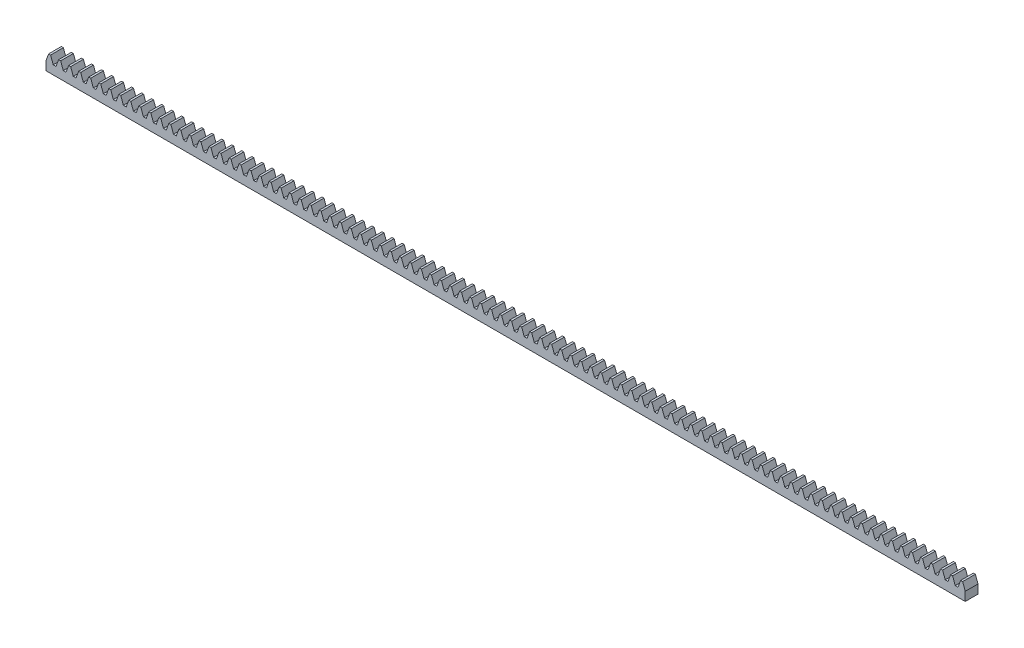
SolidWorks part; units mm, degrees
ref_plane "Front Plane" through (0, 0, 0) normal (0, 0, 1) x (1, 0, 0)
ref_plane "Top Plane" through (0, 0, 0) normal (0, 1, 0) x (1, 0, 0)
ref_plane "Right Plane" through (0, 0, 0) normal (1, 0, 0) x (0, 0, -1)
ref_plane "Plane1" through (0, 0, 46.6167) normal (0, 0, -1) x (-1, 0, 0)
sketch "Sketch1" plane through (0, 0, 46.6167) normal (0, 0, -1) x (-1, 0, 0)
  line L0 (-180.7837, -31.4854) -> (-182.0774, -35.0398)
  line L1 (-182.0774, -35.0398) -> (-182.0774, -39.4229)
  line L2 (-182.0774, -39.4229) -> (325.9226, -39.4229)
  line L3 (325.9226, -39.4229) -> (325.9226, -35.0573)
  line L4 (325.9226, -35.0573) -> (325.2266, -35.0573)
  line L5 (325.2266, -35.0573) -> (323.9265, -31.4854)
  line L6 (323.9265, -31.4854) -> (322.9314, -31.4854)
  line L7 (322.9314, -31.4854) -> (321.6313, -35.0573)
  line L8 (321.6313, -35.0573) -> (320.2393, -35.0573)
  line L9 (320.2393, -35.0573) -> (318.9392, -31.4854)
  line L10 (318.9392, -31.4854) -> (317.9441, -31.4854)
  line L11 (317.9441, -31.4854) -> (316.644, -35.0573)
  line L12 (316.644, -35.0573) -> (315.252, -35.0573)
  line L13 (315.252, -35.0573) -> (313.952, -31.4854)
  line L14 (313.952, -31.4854) -> (312.9568, -31.4854)
  line L15 (312.9568, -31.4854) -> (311.6568, -35.0573)
  line L16 (311.6568, -35.0573) -> (310.2647, -35.0573)
  line L17 (310.2647, -35.0573) -> (308.9647, -31.4854)
  line L18 (308.9647, -31.4854) -> (307.9695, -31.4854)
  line L19 (307.9695, -31.4854) -> (306.6695, -35.0573)
  line L20 (306.6695, -35.0573) -> (305.2775, -35.0573)
  line L21 (305.2775, -35.0573) -> (303.9774, -31.4854)
  line L22 (303.9774, -31.4854) -> (302.9823, -31.4854)
  line L23 (302.9823, -31.4854) -> (301.6822, -35.0573)
  line L24 (301.6822, -35.0573) -> (300.2902, -35.0573)
  line L25 (300.2902, -35.0573) -> (298.9901, -31.4854)
  line L26 (298.9901, -31.4854) -> (297.995, -31.4854)
  line L27 (297.995, -31.4854) -> (296.6949, -35.0573)
  line L28 (296.6949, -35.0573) -> (295.3029, -35.0573)
  line L29 (295.3029, -35.0573) -> (294.0028, -31.4854)
  line L30 (294.0028, -31.4854) -> (293.0077, -31.4854)
  line L31 (293.0077, -31.4854) -> (291.7076, -35.0573)
  line L32 (291.7076, -35.0573) -> (290.3156, -35.0573)
  line L33 (290.3156, -35.0573) -> (289.0156, -31.4854)
  line L34 (289.0156, -31.4854) -> (288.0204, -31.4854)
  line L35 (288.0204, -31.4854) -> (286.7204, -35.0573)
  line L36 (286.7204, -35.0573) -> (285.3283, -35.0573)
  line L37 (285.3283, -35.0573) -> (284.0283, -31.4854)
  line L38 (284.0283, -31.4854) -> (283.0331, -31.4854)
  line L39 (283.0331, -31.4854) -> (281.7331, -35.0573)
  line L40 (281.7331, -35.0573) -> (280.3411, -35.0573)
  line L41 (280.3411, -35.0573) -> (279.041, -31.4854)
  line L42 (279.041, -31.4854) -> (278.0459, -31.4854)
  line L43 (278.0459, -31.4854) -> (276.7458, -35.0573)
  line L44 (276.7458, -35.0573) -> (275.3538, -35.0573)
  line L45 (275.3538, -35.0573) -> (274.0537, -31.4854)
  line L46 (274.0537, -31.4854) -> (273.0586, -31.4854)
  line L47 (273.0586, -31.4854) -> (271.7585, -35.0573)
  line L48 (271.7585, -35.0573) -> (270.3665, -35.0573)
  line L49 (270.3665, -35.0573) -> (269.0664, -31.4854)
  line L50 (269.0664, -31.4854) -> (268.0713, -31.4854)
  line L51 (268.0713, -31.4854) -> (266.7713, -35.0573)
  line L52 (266.7713, -35.0573) -> (265.3792, -35.0573)
  line L53 (265.3792, -35.0573) -> (264.0792, -31.4854)
  line L54 (264.0792, -31.4854) -> (263.084, -31.4854)
  line L55 (263.084, -31.4854) -> (261.784, -35.0573)
  line L56 (261.784, -35.0573) -> (260.3919, -35.0573)
  line L57 (260.3919, -35.0573) -> (259.0919, -31.4854)
  line L58 (259.0919, -31.4854) -> (258.0968, -31.4854)
  line L59 (258.0968, -31.4854) -> (256.7967, -35.0573)
  line L60 (256.7967, -35.0573) -> (255.4047, -35.0573)
  line L61 (255.4047, -35.0573) -> (254.1046, -31.4854)
  line L62 (254.1046, -31.4854) -> (253.1095, -31.4854)
  line L63 (253.1095, -31.4854) -> (251.8094, -35.0573)
  line L64 (251.8094, -35.0573) -> (250.4174, -35.0573)
  line L65 (250.4174, -35.0573) -> (249.1173, -31.4854)
  line L66 (249.1173, -31.4854) -> (248.1222, -31.4854)
  line L67 (248.1222, -31.4854) -> (246.8221, -35.0573)
  line L68 (246.8221, -35.0573) -> (245.4301, -35.0573)
  line L69 (245.4301, -35.0573) -> (244.1301, -31.4854)
  line L70 (244.1301, -31.4854) -> (243.1349, -31.4854)
  line L71 (243.1349, -31.4854) -> (241.8349, -35.0573)
  line L72 (241.8349, -35.0573) -> (240.4428, -35.0573)
  line L73 (240.4428, -35.0573) -> (239.1428, -31.4854)
  line L74 (239.1428, -31.4854) -> (238.1476, -31.4854)
  line L75 (238.1476, -31.4854) -> (236.8476, -35.0573)
  line L76 (236.8476, -35.0573) -> (235.4556, -35.0573)
  line L77 (235.4556, -35.0573) -> (234.1555, -31.4854)
  line L78 (234.1555, -31.4854) -> (233.1604, -31.4854)
  line L79 (233.1604, -31.4854) -> (231.8603, -35.0573)
  line L80 (231.8603, -35.0573) -> (230.4683, -35.0573)
  line L81 (230.4683, -35.0573) -> (229.1682, -31.4854)
  line L82 (229.1682, -31.4854) -> (228.1731, -31.4854)
  line L83 (228.1731, -31.4854) -> (226.873, -35.0573)
  line L84 (226.873, -35.0573) -> (225.481, -35.0573)
  line L85 (225.481, -35.0573) -> (224.1809, -31.4854)
  line L86 (224.1809, -31.4854) -> (223.1858, -31.4854)
  line L87 (223.1858, -31.4854) -> (221.8858, -35.0573)
  line L88 (221.8858, -35.0573) -> (220.4937, -35.0573)
  line L89 (220.4937, -35.0573) -> (219.1937, -31.4854)
  line L90 (219.1937, -31.4854) -> (218.1985, -31.4854)
  line L91 (218.1985, -31.4854) -> (216.8985, -35.0573)
  line L92 (216.8985, -35.0573) -> (215.5064, -35.0573)
  line L93 (215.5064, -35.0573) -> (214.2064, -31.4854)
  line L94 (214.2064, -31.4854) -> (213.2113, -31.4854)
  line L95 (213.2113, -31.4854) -> (211.9112, -35.0573)
  line L96 (211.9112, -35.0573) -> (210.5192, -35.0573)
  line L97 (210.5192, -35.0573) -> (209.2191, -31.4854)
  line L98 (209.2191, -31.4854) -> (208.224, -31.4854)
  line L99 (208.224, -31.4854) -> (206.9239, -35.0573)
  line L100 (206.9239, -35.0573) -> (205.5319, -35.0573)
  line L101 (205.5319, -35.0573) -> (204.2318, -31.4854)
  line L102 (204.2318, -31.4854) -> (203.2367, -31.4854)
  line L103 (203.2367, -31.4854) -> (201.9366, -35.0573)
  line L104 (201.9366, -35.0573) -> (200.5446, -35.0573)
  line L105 (200.5446, -35.0573) -> (199.2446, -31.4854)
  line L106 (199.2446, -31.4854) -> (198.2494, -31.4854)
  line L107 (198.2494, -31.4854) -> (196.9494, -35.0573)
  line L108 (196.9494, -35.0573) -> (195.5573, -35.0573)
  line L109 (195.5573, -35.0573) -> (194.2573, -31.4854)
  line L110 (194.2573, -31.4854) -> (193.2621, -31.4854)
  line L111 (193.2621, -31.4854) -> (191.9621, -35.0573)
  line L112 (191.9621, -35.0573) -> (190.5701, -35.0573)
  line L113 (190.5701, -35.0573) -> (189.27, -31.4854)
  line L114 (189.27, -31.4854) -> (188.2749, -31.4854)
  line L115 (188.2749, -31.4854) -> (186.9748, -35.0573)
  line L116 (186.9748, -35.0573) -> (185.5828, -35.0573)
  line L117 (185.5828, -35.0573) -> (184.2827, -31.4854)
  line L118 (184.2827, -31.4854) -> (183.2876, -31.4854)
  line L119 (183.2876, -31.4854) -> (181.9875, -35.0573)
  line L120 (181.9875, -35.0573) -> (180.5955, -35.0573)
  line L121 (180.5955, -35.0573) -> (179.2954, -31.4854)
  line L122 (179.2954, -31.4854) -> (178.3003, -31.4854)
  line L123 (178.3003, -31.4854) -> (177.0002, -35.0573)
  line L124 (177.0002, -35.0573) -> (175.6082, -35.0573)
  line L125 (175.6082, -35.0573) -> (174.3082, -31.4854)
  line L126 (174.3082, -31.4854) -> (173.313, -31.4854)
  line L127 (173.313, -31.4854) -> (172.013, -35.0573)
  line L128 (172.013, -35.0573) -> (170.6209, -35.0573)
  line L129 (170.6209, -35.0573) -> (169.3209, -31.4854)
  line L130 (169.3209, -31.4854) -> (168.3257, -31.4854)
  line L131 (168.3257, -31.4854) -> (167.0257, -35.0573)
  line L132 (167.0257, -35.0573) -> (165.6337, -35.0573)
  line L133 (165.6337, -35.0573) -> (164.3336, -31.4854)
  line L134 (164.3336, -31.4854) -> (163.3385, -31.4854)
  line L135 (163.3385, -31.4854) -> (162.0384, -35.0573)
  line L136 (162.0384, -35.0573) -> (160.6464, -35.0573)
  line L137 (160.6464, -35.0573) -> (159.3463, -31.4854)
  line L138 (159.3463, -31.4854) -> (158.3512, -31.4854)
  line L139 (158.3512, -31.4854) -> (157.0511, -35.0573)
  line L140 (157.0511, -35.0573) -> (155.6591, -35.0573)
  line L141 (155.6591, -35.0573) -> (154.359, -31.4854)
  line L142 (154.359, -31.4854) -> (153.3639, -31.4854)
  line L143 (153.3639, -31.4854) -> (152.0639, -35.0573)
  line L144 (152.0639, -35.0573) -> (150.6718, -35.0573)
  line L145 (150.6718, -35.0573) -> (149.3718, -31.4854)
  line L146 (149.3718, -31.4854) -> (148.3766, -31.4854)
  line L147 (148.3766, -31.4854) -> (147.0766, -35.0573)
  line L148 (147.0766, -35.0573) -> (145.6845, -35.0573)
  line L149 (145.6845, -35.0573) -> (144.3845, -31.4854)
  line L150 (144.3845, -31.4854) -> (143.3894, -31.4854)
  line L151 (143.3894, -31.4854) -> (142.0893, -35.0573)
  line L152 (142.0893, -35.0573) -> (140.6973, -35.0573)
  line L153 (140.6973, -35.0573) -> (139.3972, -31.4854)
  line L154 (139.3972, -31.4854) -> (138.4021, -31.4854)
  line L155 (138.4021, -31.4854) -> (137.102, -35.0573)
  line L156 (137.102, -35.0573) -> (135.71, -35.0573)
  line L157 (135.71, -35.0573) -> (134.4099, -31.4854)
  line L158 (134.4099, -31.4854) -> (133.4148, -31.4854)
  line L159 (133.4148, -31.4854) -> (132.1147, -35.0573)
  line L160 (132.1147, -35.0573) -> (130.7227, -35.0573)
  line L161 (130.7227, -35.0573) -> (129.4227, -31.4854)
  line L162 (129.4227, -31.4854) -> (128.4275, -31.4854)
  line L163 (128.4275, -31.4854) -> (127.1275, -35.0573)
  line L164 (127.1275, -35.0573) -> (125.7354, -35.0573)
  line L165 (125.7354, -35.0573) -> (124.4354, -31.4854)
  line L166 (124.4354, -31.4854) -> (123.4402, -31.4854)
  line L167 (123.4402, -31.4854) -> (122.1402, -35.0573)
  line L168 (122.1402, -35.0573) -> (120.7482, -35.0573)
  line L169 (120.7482, -35.0573) -> (119.4481, -31.4854)
  line L170 (119.4481, -31.4854) -> (118.453, -31.4854)
  line L171 (118.453, -31.4854) -> (117.1529, -35.0573)
  line L172 (117.1529, -35.0573) -> (115.7609, -35.0573)
  line L173 (115.7609, -35.0573) -> (114.4608, -31.4854)
  line L174 (114.4608, -31.4854) -> (113.4657, -31.4854)
  line L175 (113.4657, -31.4854) -> (112.1656, -35.0573)
  line L176 (112.1656, -35.0573) -> (110.7736, -35.0573)
  line L177 (110.7736, -35.0573) -> (109.4735, -31.4854)
  line L178 (109.4735, -31.4854) -> (108.4784, -31.4854)
  line L179 (108.4784, -31.4854) -> (107.1784, -35.0573)
  line L180 (107.1784, -35.0573) -> (105.7863, -35.0573)
  line L181 (105.7863, -35.0573) -> (104.4863, -31.4854)
  line L182 (104.4863, -31.4854) -> (103.4911, -31.4854)
  line L183 (103.4911, -31.4854) -> (102.1911, -35.0573)
  line L184 (102.1911, -35.0573) -> (100.799, -35.0573)
  line L185 (100.799, -35.0573) -> (99.499, -31.4854)
  line L186 (99.499, -31.4854) -> (98.5039, -31.4854)
  line L187 (98.5039, -31.4854) -> (97.2038, -35.0573)
  line L188 (97.2038, -35.0573) -> (95.8118, -35.0573)
  line L189 (95.8118, -35.0573) -> (94.5117, -31.4854)
  line L190 (94.5117, -31.4854) -> (93.5166, -31.4854)
  line L191 (93.5166, -31.4854) -> (92.2165, -35.0573)
  line L192 (92.2165, -35.0573) -> (90.8245, -35.0573)
  line L193 (90.8245, -35.0573) -> (89.5244, -31.4854)
  line L194 (89.5244, -31.4854) -> (88.5293, -31.4854)
  line L195 (88.5293, -31.4854) -> (87.2292, -35.0573)
  line L196 (87.2292, -35.0573) -> (85.8372, -35.0573)
  line L197 (85.8372, -35.0573) -> (84.5371, -31.4854)
  line L198 (84.5371, -31.4854) -> (83.542, -31.4854)
  line L199 (83.542, -31.4854) -> (82.242, -35.0573)
  line L200 (82.242, -35.0573) -> (80.8499, -35.0573)
  line L201 (80.8499, -35.0573) -> (79.5499, -31.4854)
  line L202 (79.5499, -31.4854) -> (78.5547, -31.4854)
  line L203 (78.5547, -31.4854) -> (77.2547, -35.0573)
  line L204 (77.2547, -35.0573) -> (75.8626, -35.0573)
  line L205 (75.8626, -35.0573) -> (74.5626, -31.4854)
  line L206 (74.5626, -31.4854) -> (73.5675, -31.4854)
  line L207 (73.5675, -31.4854) -> (72.2674, -35.0573)
  line L208 (72.2674, -35.0573) -> (70.8754, -35.0573)
  line L209 (70.8754, -35.0573) -> (69.5753, -31.4854)
  line L210 (69.5753, -31.4854) -> (68.5802, -31.4854)
  line L211 (68.5802, -31.4854) -> (67.2801, -35.0573)
  line L212 (67.2801, -35.0573) -> (65.8881, -35.0573)
  line L213 (65.8881, -35.0573) -> (64.588, -31.4854)
  line L214 (64.588, -31.4854) -> (63.5929, -31.4854)
  line L215 (63.5929, -31.4854) -> (62.2928, -35.0573)
  line L216 (62.2928, -35.0573) -> (60.9008, -35.0573)
  line L217 (60.9008, -35.0573) -> (59.6008, -31.4854)
  line L218 (59.6008, -31.4854) -> (58.6056, -31.4854)
  line L219 (58.6056, -31.4854) -> (57.3056, -35.0573)
  line L220 (57.3056, -35.0573) -> (55.9135, -35.0573)
  line L221 (55.9135, -35.0573) -> (54.6135, -31.4854)
  line L222 (54.6135, -31.4854) -> (53.6183, -31.4854)
  line L223 (53.6183, -31.4854) -> (52.3183, -35.0573)
  line L224 (52.3183, -35.0573) -> (50.9263, -35.0573)
  line L225 (50.9263, -35.0573) -> (49.6262, -31.4854)
  line L226 (49.6262, -31.4854) -> (48.6311, -31.4854)
  line L227 (48.6311, -31.4854) -> (47.331, -35.0573)
  line L228 (47.331, -35.0573) -> (45.939, -35.0573)
  line L229 (45.939, -35.0573) -> (44.6389, -31.4854)
  line L230 (44.6389, -31.4854) -> (43.6438, -31.4854)
  line L231 (43.6438, -31.4854) -> (42.3437, -35.0573)
  line L232 (42.3437, -35.0573) -> (40.9517, -35.0573)
  line L233 (40.9517, -35.0573) -> (39.6516, -31.4854)
  line L234 (39.6516, -31.4854) -> (38.6565, -31.4854)
  line L235 (38.6565, -31.4854) -> (37.3565, -35.0573)
  line L236 (37.3565, -35.0573) -> (35.9644, -35.0573)
  line L237 (35.9644, -35.0573) -> (34.6644, -31.4854)
  line L238 (34.6644, -31.4854) -> (33.6692, -31.4854)
  line L239 (33.6692, -31.4854) -> (32.3692, -35.0573)
  line L240 (32.3692, -35.0573) -> (30.9771, -35.0573)
  line L241 (30.9771, -35.0573) -> (29.6771, -31.4854)
  line L242 (29.6771, -31.4854) -> (28.682, -31.4854)
  line L243 (28.682, -31.4854) -> (27.3819, -35.0573)
  line L244 (27.3819, -35.0573) -> (25.9899, -35.0573)
  line L245 (25.9899, -35.0573) -> (24.6898, -31.4854)
  line L246 (24.6898, -31.4854) -> (23.6947, -31.4854)
  line L247 (23.6947, -31.4854) -> (22.3946, -35.0573)
  line L248 (22.3946, -35.0573) -> (21.0026, -35.0573)
  line L249 (21.0026, -35.0573) -> (19.7025, -31.4854)
  line L250 (19.7025, -31.4854) -> (18.7074, -31.4854)
  line L251 (18.7074, -31.4854) -> (17.4073, -35.0573)
  line L252 (17.4073, -35.0573) -> (16.0153, -35.0573)
  line L253 (16.0153, -35.0573) -> (14.7153, -31.4854)
  line L254 (14.7153, -31.4854) -> (13.7201, -31.4854)
  line L255 (13.7201, -31.4854) -> (12.4201, -35.0573)
  line L256 (12.4201, -35.0573) -> (11.028, -35.0573)
  line L257 (11.028, -35.0573) -> (9.728, -31.4854)
  line L258 (9.728, -31.4854) -> (8.7328, -31.4854)
  line L259 (8.7328, -31.4854) -> (7.4328, -35.0573)
  line L260 (7.4328, -35.0573) -> (6.0408, -35.0573)
  line L261 (6.0408, -35.0573) -> (4.7407, -31.4854)
  line L262 (4.7407, -31.4854) -> (3.7456, -31.4854)
  line L263 (3.7456, -31.4854) -> (2.4455, -35.0573)
  line L264 (2.4455, -35.0573) -> (1.0535, -35.0573)
  line L265 (1.0535, -35.0573) -> (-0.2466, -31.4854)
  line L266 (-0.2466, -31.4854) -> (-1.2417, -31.4854)
  line L267 (-1.2417, -31.4854) -> (-2.5418, -35.0573)
  line L268 (-2.5418, -35.0573) -> (-3.9338, -35.0573)
  line L269 (-3.9338, -35.0573) -> (-5.2339, -31.4854)
  line L270 (-5.2339, -31.4854) -> (-6.229, -31.4854)
  line L271 (-6.229, -31.4854) -> (-7.5291, -35.0573)
  line L272 (-7.5291, -35.0573) -> (-8.9211, -35.0573)
  line L273 (-8.9211, -35.0573) -> (-10.2211, -31.4854)
  line L274 (-10.2211, -31.4854) -> (-11.2163, -31.4854)
  line L275 (-11.2163, -31.4854) -> (-12.5163, -35.0573)
  line L276 (-12.5163, -35.0573) -> (-13.9084, -35.0573)
  line L277 (-13.9084, -35.0573) -> (-15.2084, -31.4854)
  line L278 (-15.2084, -31.4854) -> (-16.2036, -31.4854)
  line L279 (-16.2036, -31.4854) -> (-17.5036, -35.0573)
  line L280 (-17.5036, -35.0573) -> (-18.8956, -35.0573)
  line L281 (-18.8956, -35.0573) -> (-20.1957, -31.4854)
  line L282 (-20.1957, -31.4854) -> (-21.1908, -31.4854)
  line L283 (-21.1908, -31.4854) -> (-22.4909, -35.0573)
  line L284 (-22.4909, -35.0573) -> (-23.8829, -35.0573)
  line L285 (-23.8829, -35.0573) -> (-25.183, -31.4854)
  line L286 (-25.183, -31.4854) -> (-26.1781, -31.4854)
  line L287 (-26.1781, -31.4854) -> (-27.4782, -35.0573)
  line L288 (-27.4782, -35.0573) -> (-28.8702, -35.0573)
  line L289 (-28.8702, -35.0573) -> (-30.1703, -31.4854)
  line L290 (-30.1703, -31.4854) -> (-31.1654, -31.4854)
  line L291 (-31.1654, -31.4854) -> (-32.4654, -35.0573)
  line L292 (-32.4654, -35.0573) -> (-33.8575, -35.0573)
  line L293 (-33.8575, -35.0573) -> (-35.1575, -31.4854)
  line L294 (-35.1575, -31.4854) -> (-36.1527, -31.4854)
  line L295 (-36.1527, -31.4854) -> (-37.4527, -35.0573)
  line L296 (-37.4527, -35.0573) -> (-38.8448, -35.0573)
  line L297 (-38.8448, -35.0573) -> (-40.1448, -31.4854)
  line L298 (-40.1448, -31.4854) -> (-41.1399, -31.4854)
  line L299 (-41.1399, -31.4854) -> (-42.44, -35.0573)
  line L300 (-42.44, -35.0573) -> (-43.832, -35.0573)
  line L301 (-43.832, -35.0573) -> (-45.1321, -31.4854)
  line L302 (-45.1321, -31.4854) -> (-46.1272, -31.4854)
  line L303 (-46.1272, -31.4854) -> (-47.4273, -35.0573)
  line L304 (-47.4273, -35.0573) -> (-48.8193, -35.0573)
  line L305 (-48.8193, -35.0573) -> (-50.1194, -31.4854)
  line L306 (-50.1194, -31.4854) -> (-51.1145, -31.4854)
  line L307 (-51.1145, -31.4854) -> (-52.4146, -35.0573)
  line L308 (-52.4146, -35.0573) -> (-53.8066, -35.0573)
  line L309 (-53.8066, -35.0573) -> (-55.1066, -31.4854)
  line L310 (-55.1066, -31.4854) -> (-56.1018, -31.4854)
  line L311 (-56.1018, -31.4854) -> (-57.4018, -35.0573)
  line L312 (-57.4018, -35.0573) -> (-58.7939, -35.0573)
  line L313 (-58.7939, -35.0573) -> (-60.0939, -31.4854)
  line L314 (-60.0939, -31.4854) -> (-61.0891, -31.4854)
  line L315 (-61.0891, -31.4854) -> (-62.3891, -35.0573)
  line L316 (-62.3891, -35.0573) -> (-63.7811, -35.0573)
  line L317 (-63.7811, -35.0573) -> (-65.0812, -31.4854)
  line L318 (-65.0812, -31.4854) -> (-66.0763, -31.4854)
  line L319 (-66.0763, -31.4854) -> (-67.3764, -35.0573)
  line L320 (-67.3764, -35.0573) -> (-68.7684, -35.0573)
  line L321 (-68.7684, -35.0573) -> (-70.0685, -31.4854)
  line L322 (-70.0685, -31.4854) -> (-71.0636, -31.4854)
  line L323 (-71.0636, -31.4854) -> (-72.3637, -35.0573)
  line L324 (-72.3637, -35.0573) -> (-73.7557, -35.0573)
  line L325 (-73.7557, -35.0573) -> (-75.0558, -31.4854)
  line L326 (-75.0558, -31.4854) -> (-76.0509, -31.4854)
  line L327 (-76.0509, -31.4854) -> (-77.3509, -35.0573)
  line L328 (-77.3509, -35.0573) -> (-78.743, -35.0573)
  line L329 (-78.743, -35.0573) -> (-80.043, -31.4854)
  line L330 (-80.043, -31.4854) -> (-81.0382, -31.4854)
  line L331 (-81.0382, -31.4854) -> (-82.3382, -35.0573)
  line L332 (-82.3382, -35.0573) -> (-83.7303, -35.0573)
  line L333 (-83.7303, -35.0573) -> (-85.0303, -31.4854)
  line L334 (-85.0303, -31.4854) -> (-86.0254, -31.4854)
  line L335 (-86.0254, -31.4854) -> (-87.3255, -35.0573)
  line L336 (-87.3255, -35.0573) -> (-88.7175, -35.0573)
  line L337 (-88.7175, -35.0573) -> (-90.0176, -31.4854)
  line L338 (-90.0176, -31.4854) -> (-91.0127, -31.4854)
  line L339 (-91.0127, -31.4854) -> (-92.3128, -35.0573)
  line L340 (-92.3128, -35.0573) -> (-93.7048, -35.0573)
  line L341 (-93.7048, -35.0573) -> (-95.0049, -31.4854)
  line L342 (-95.0049, -31.4854) -> (-96, -31.4854)
  line L343 (-96, -31.4854) -> (-97.3001, -35.0573)
  line L344 (-97.3001, -35.0573) -> (-98.6921, -35.0573)
  line L345 (-98.6921, -35.0573) -> (-99.9921, -31.4854)
  line L346 (-99.9921, -31.4854) -> (-100.9873, -31.4854)
  line L347 (-100.9873, -31.4854) -> (-102.2873, -35.0573)
  line L348 (-102.2873, -35.0573) -> (-103.6794, -35.0573)
  line L349 (-103.6794, -35.0573) -> (-104.9794, -31.4854)
  line L350 (-104.9794, -31.4854) -> (-105.9746, -31.4854)
  line L351 (-105.9746, -31.4854) -> (-107.2746, -35.0573)
  line L352 (-107.2746, -35.0573) -> (-108.6666, -35.0573)
  line L353 (-108.6666, -35.0573) -> (-109.9667, -31.4854)
  line L354 (-109.9667, -31.4854) -> (-110.9618, -31.4854)
  line L355 (-110.9618, -31.4854) -> (-112.2619, -35.0573)
  line L356 (-112.2619, -35.0573) -> (-113.6539, -35.0573)
  line L357 (-113.6539, -35.0573) -> (-114.954, -31.4854)
  line L358 (-114.954, -31.4854) -> (-115.9491, -31.4854)
  line L359 (-115.9491, -31.4854) -> (-117.2492, -35.0573)
  line L360 (-117.2492, -35.0573) -> (-118.6412, -35.0573)
  line L361 (-118.6412, -35.0573) -> (-119.9413, -31.4854)
  line L362 (-119.9413, -31.4854) -> (-120.9364, -31.4854)
  line L363 (-120.9364, -31.4854) -> (-122.2365, -35.0573)
  line L364 (-122.2365, -35.0573) -> (-123.6285, -35.0573)
  line L365 (-123.6285, -35.0573) -> (-124.9285, -31.4854)
  line L366 (-124.9285, -31.4854) -> (-125.9237, -31.4854)
  line L367 (-125.9237, -31.4854) -> (-127.2237, -35.0573)
  line L368 (-127.2237, -35.0573) -> (-128.6158, -35.0573)
  line L369 (-128.6158, -35.0573) -> (-129.9158, -31.4854)
  line L370 (-129.9158, -31.4854) -> (-130.911, -31.4854)
  line L371 (-130.911, -31.4854) -> (-132.211, -35.0573)
  line L372 (-132.211, -35.0573) -> (-133.603, -35.0573)
  line L373 (-133.603, -35.0573) -> (-134.9031, -31.4854)
  line L374 (-134.9031, -31.4854) -> (-135.8982, -31.4854)
  line L375 (-135.8982, -31.4854) -> (-137.1983, -35.0573)
  line L376 (-137.1983, -35.0573) -> (-138.5903, -35.0573)
  line L377 (-138.5903, -35.0573) -> (-139.8904, -31.4854)
  line L378 (-139.8904, -31.4854) -> (-140.8855, -31.4854)
  line L379 (-140.8855, -31.4854) -> (-142.1856, -35.0573)
  line L380 (-142.1856, -35.0573) -> (-143.5776, -35.0573)
  line L381 (-143.5776, -35.0573) -> (-144.8777, -31.4854)
  line L382 (-144.8777, -31.4854) -> (-145.8728, -31.4854)
  line L383 (-145.8728, -31.4854) -> (-147.1728, -35.0573)
  line L384 (-147.1728, -35.0573) -> (-148.5649, -35.0573)
  line L385 (-148.5649, -35.0573) -> (-149.8649, -31.4854)
  line L386 (-149.8649, -31.4854) -> (-150.8601, -31.4854)
  line L387 (-150.8601, -31.4854) -> (-152.1601, -35.0573)
  line L388 (-152.1601, -35.0573) -> (-153.5522, -35.0573)
  line L389 (-153.5522, -35.0573) -> (-154.8522, -31.4854)
  line L390 (-154.8522, -31.4854) -> (-155.8473, -31.4854)
  line L391 (-155.8473, -31.4854) -> (-157.1474, -35.0573)
  line L392 (-157.1474, -35.0573) -> (-158.5394, -35.0573)
  line L393 (-158.5394, -35.0573) -> (-159.8395, -31.4854)
  line L394 (-159.8395, -31.4854) -> (-160.8346, -31.4854)
  line L395 (-160.8346, -31.4854) -> (-162.1347, -35.0573)
  line L396 (-162.1347, -35.0573) -> (-163.5267, -35.0573)
  line L397 (-163.5267, -35.0573) -> (-164.8268, -31.4854)
  line L398 (-164.8268, -31.4854) -> (-165.8219, -31.4854)
  line L399 (-165.8219, -31.4854) -> (-167.122, -35.0573)
  line L400 (-167.122, -35.0573) -> (-168.514, -35.0573)
  line L401 (-168.514, -35.0573) -> (-169.814, -31.4854)
  line L402 (-169.814, -31.4854) -> (-170.8092, -31.4854)
  line L403 (-170.8092, -31.4854) -> (-172.1092, -35.0573)
  line L404 (-172.1092, -35.0573) -> (-173.5013, -35.0573)
  line L405 (-173.5013, -35.0573) -> (-174.8013, -31.4854)
  line L406 (-174.8013, -31.4854) -> (-175.7965, -31.4854)
  line L407 (-175.7965, -31.4854) -> (-177.0965, -35.0573)
  line L408 (-177.0965, -35.0573) -> (-178.4885, -35.0573)
  line L409 (-178.4885, -35.0573) -> (-179.7886, -31.4854)
  line L410 (-179.7886, -31.4854) -> (-180.7837, -31.4854)
extrude "Boss-Extrude1" add sketch "Sketch1" against normal blind 6.35
sketch "Sketch2" plane through (0, 0, 52.9667) normal (0, 0, 1) x (1, 0, 0)
  line L1 (-325.9226, -39.4229) -> (-275.3538, -39.4229)
  line L2 (-325.9226, -39.4229) -> (-325.9226, -35.0573)
  line L4 (-275.3538, -39.4229) -> (-275.3538, -35.0573)
  line L6 (-325.9226, -35.0573) -> (-325.9226, -29.0399)
  line L7 (-325.9226, -29.0399) -> (-275.3538, -29.0399)
  line L8 (-275.3538, -35.0573) -> (-275.3538, -29.0399)
  dimension "D1" = 6.0174
  dimension "D2" = 10.383
extrude "Cut-Extrude1" cut sketch "Sketch2" against normal through all
